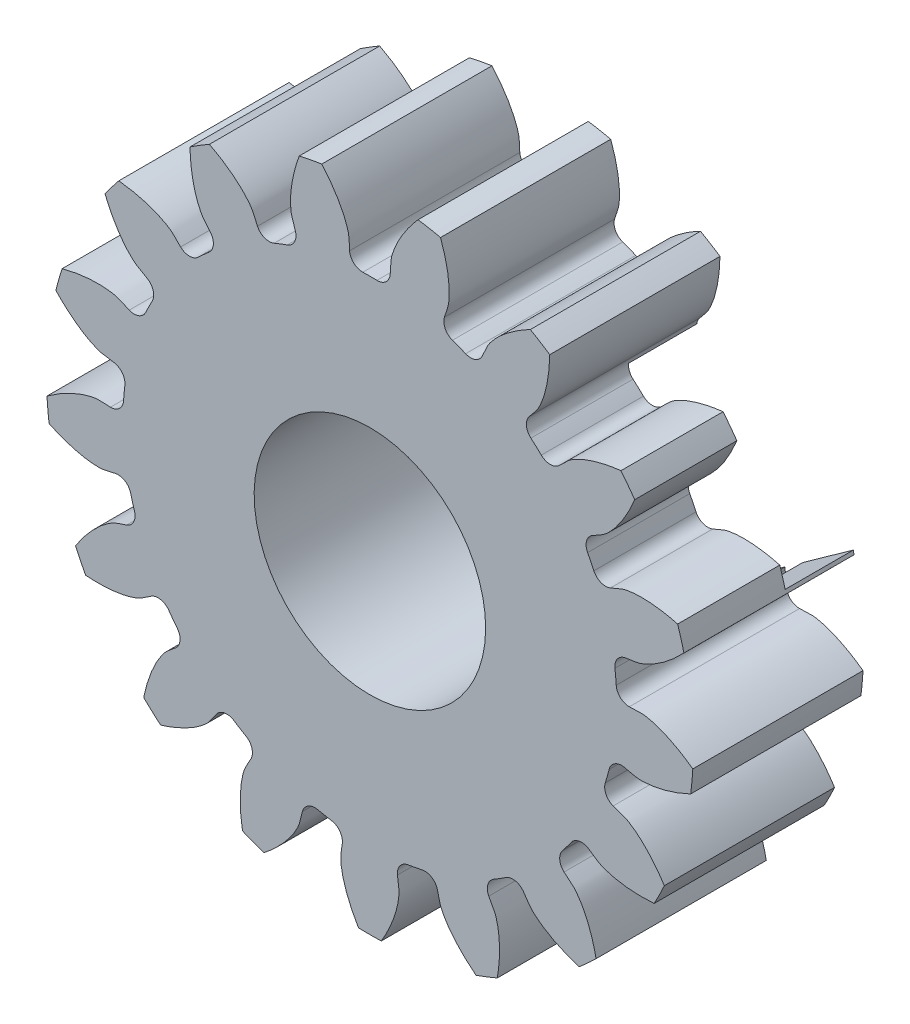
SolidWorks part; units mm, degrees
material "POM 乙缩醛共聚物"
ref_plane "前视基准面" through (0, 0, 0) normal (0, 0, 1) x (1, 0, 0)
ref_plane "上视基准面" through (0, 0, 0) normal (0, 1, 0) x (1, 0, 0)
ref_plane "右视基准面" through (0, 0, 0) normal (1, 0, 0) x (0, 0, -1)
other "Configuration Table"
ref_axis "Axis1" through (0, 0, -88.99) along (0, 0, 1)
sketch "草图1" plane through (0, 0, 0) normal (0, 0, 1) x (1, 0, 0)
  circle A0 centre (0, 0) radius 9.5
extrude "LaShenA" add sketch "草图1" along normal blind 5
sketch "SketchA" plane through (0, 0, 5) normal (0, 0, 1) x (1, 0, 0)
  line L0 (0, 0) -> (0, 9.5) construction
  arc A0 (0.207, 7.247) -> (-0.207, 7.247) centre (0, 0) ccw
  arc A1 (1.9284, 9.9057) -> (-1.9284, 9.9057) centre (0, 0) ccw
  arc A2 (-0.207, 7.247) -> (-0.5968, 7.5982) centre (-0.2179, 7.6269) cw
  arc A3 (0.5968, 7.5982) -> (0.207, 7.247) centre (0.2179, 7.6269) cw
  circle A4 centre (0, 0) radius 7.9874 construction
  circle A5 centre (0, 0) radius 9.5 construction
  circle A6 centre (0, 0) radius 7.25 construction
  circle A7 centre (0, 0) radius 8.5 construction
  spline S0 degree 3 poles (0.5968, 7.5982) (0.606, 7.7206) (0.6026, 7.8698) (0.6296, 8.029) (0.6422, 8.0808) (0.6533, 8.1218) (0.6675, 8.1687) (0.685, 8.2214) (0.7063, 8.2797) (0.7317, 8.3435) (0.7614, 8.4125) (0.7959, 8.4865) (0.8354, 8.5654) (0.8802, 8.6489) (0.9307, 8.7367) (0.987, 8.8286) (1.0495, 8.9244) (1.1185, 9.0236) (1.1941, 9.1262) (1.2767, 9.2316) (1.3664, 9.3397) (1.4635, 9.4501) (1.5682, 9.5624) (1.7212, 9.7175) (1.8433, 9.8309) (1.9284, 9.9057) knots 0.121184 0.121184 0.121184 0.121184 0.238206 0.264317 0.275812 0.289397 0.305072 0.322837 0.342692 0.364637 0.388672 0.414798 0.443013 0.473318 0.505713 0.540198 0.576773 0.615438 0.656194 0.699039 0.743974 0.790999 0.840114 0.89132 1 1 1 1
  spline S1 degree 3 poles (-0.5968, 7.5982) (-0.606, 7.7206) (-0.6026, 7.8698) (-0.6296, 8.029) (-0.6422, 8.0808) (-0.6533, 8.1218) (-0.6675, 8.1687) (-0.685, 8.2214) (-0.7063, 8.2797) (-0.7317, 8.3435) (-0.7614, 8.4125) (-0.7959, 8.4865) (-0.8354, 8.5654) (-0.8802, 8.6489) (-0.9307, 8.7367) (-0.987, 8.8286) (-1.0495, 8.9244) (-1.1185, 9.0236) (-1.1941, 9.1262) (-1.2767, 9.2316) (-1.3664, 9.3397) (-1.4635, 9.4501) (-1.5682, 9.5624) (-1.7212, 9.7175) (-1.8433, 9.8309) (-1.9284, 9.9057) knots 0.121184 0.121184 0.121184 0.121184 0.238206 0.264317 0.275812 0.289397 0.305072 0.322837 0.342692 0.364637 0.388672 0.414798 0.443013 0.473318 0.505713 0.540198 0.576773 0.615438 0.656194 0.699039 0.743974 0.790999 0.840114 0.89132 1 1 1 1
  dimension "D1" = 0.38
  dimension "Db" = 15.9748
  dimension "Da" = 19
  dimension "Df" = 14.5
  dimension "Dn" = 17
extrude "Cut-ExtrudeA" cut sketch "SketchA" against normal blind 5
pattern_circular "www.KYTool.cn" count 17 over 360 about axis through (0, 0, -88.99) along (0, 0, 1) of "Cut-ExtrudeA"
sketch "草图3" plane through (0, 0, 0) normal (0, 0, -1) x (-1, 0, 0)
  line L2 (-14.6995, 6.3028) -> (-1.9735, -2.7686)
  line L3 (1.4109, 3.0934) -> (-12.8082, 9.5787)
  line L4 (-14.6995, 6.3028) -> (-1.9735, -2.7686)
  line L5 (1.4109, 3.0934) -> (-12.8082, 9.5787)
  arc A2 (-1.9735, -2.7686) -> (1.4109, 3.0934) centre (0, 0) ccw
  arc A3 (-12.8082, 9.5787) -> (-14.6995, 6.3028) centre (-13.5966, 7.85) ccw
  arc A4 (-1.9735, -2.7686) -> (1.4109, 3.0934) centre (0, 0) ccw
  arc A5 (-12.8082, 9.5787) -> (-14.6995, 6.3028) centre (-13.5966, 7.85) ccw
  dimension "D1" = 0
extrude "切除-拉伸2" cut sketch "草图3" against normal up to surface (2 mm away)
sketch "草图4" plane through (0, 0, 2) normal (0, 0, -1) x (-1, 0, 0)
  circle A0 centre (0, 0) radius 3.4
extrude "切除-拉伸3" cut sketch "草图4" against normal through all both and the other way through all
